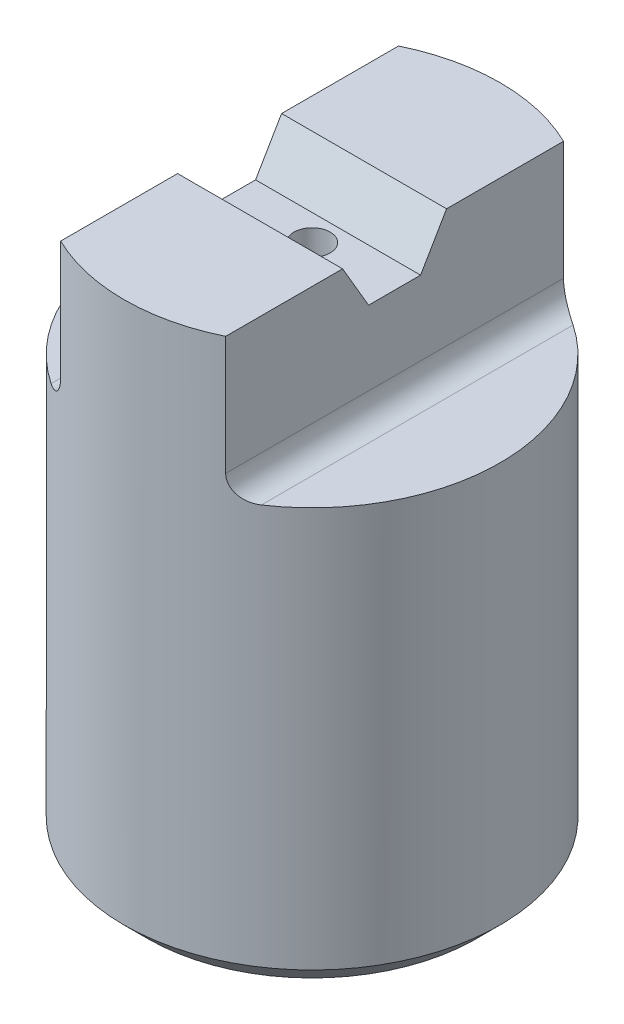
SolidWorks part; units mm, degrees
material "S7"
ref_plane "Alzado" through (0, 0, 0) normal (0, 0, 1) x (1, 0, 0)
ref_plane "Planta" through (0, 0, 0) normal (0, 1, 0) x (1, 0, 0)
ref_plane "Vista lateral" through (0, 0, 0) normal (1, 0, 0) x (0, 0, -1)
sketch "Croquis1" plane through (0, 0, 0) normal (0, 1, 0) x (1, 0, 0)
  circle A0 centre (0, 0) radius 12.6746
  dimension "D1" = 25.3492
extrude "Saliente-Extruir1" add sketch "Croquis1" along normal blind 38.1
sketch "Croquis2" plane through (0, 0, 0) normal (1, 0, 0) x (0, 0, -1)
  line L0 (-3.5052, 38.1) -> (3.5052, 38.1)
  line L1 (12.6746, 38.1) -> (-12.6746, 38.1) construction
  line L2 (3.5052, 38.1) -> (1.7526, 35.1028)
  line L3 (1.7526, 35.1028) -> (-1.7526, 35.1028)
  line L4 (-1.7526, 35.1028) -> (-3.5052, 38.1)
  line L5 (0, 0) -> (0, 35.1028) construction
  line L6 (0, 35.1028) -> (0, 38.1) construction
  dimension "D1" = 2.9972
  dimension "D2" = 3.5052
  dimension "D3" = 7.0104
extrude "Cortar-Extruir1" cut sketch "Croquis2" against normal through all both and the other way through all
sketch "Croquis3" plane through (0, 0, 0) normal (0, 0, 1) x (1, 0, 0)
  line L0 (-12.6746, 28.575) -> (-7.0866, 28.575)
  line L1 (-12.6746, 35.1028) -> (-12.6746, 0) construction
  line L2 (-5.5626, 30.099) -> (-5.5626, 38.1)
  line L3 (12.1803, 38.1) -> (-12.1803, 38.1) construction
  line L4 (-5.5626, 38.1) -> (-12.6746, 38.1)
  line L5 (-12.6746, 38.1) -> (-12.6746, 28.575)
  line L6 (0, 0) -> (0, 38.1) construction
  line L7 (-12.6746, 0) -> (12.6746, 0) construction
  line L8 (12.6746, 38.1) -> (12.6746, 28.575)
  line L9 (5.5626, 38.1) -> (12.6746, 38.1)
  line L10 (5.5626, 30.099) -> (5.5626, 38.1)
  line L11 (12.6746, 28.575) -> (7.0866, 28.575)
  arc A0 (-7.0866, 28.575) -> (-5.5626, 30.099) centre (-7.0866, 30.099) ccw
  arc A1 (7.0866, 28.575) -> (5.5626, 30.099) centre (7.0866, 30.099) cw
  dimension "D1" = 1.524
  dimension "D2" = 9.525
  dimension "D3" = 11.1252
extrude "Cortar-Extruir2" cut sketch "Croquis3" against normal through all both and the other way through all
chamfer "Chaflán1" distance 1.5875 angle 45 1 edges at (0, 0, 12.6746)
sketch "Croquis4" plane through (0, 0, 0) normal (0, -1, 0) x (1, 0, 0)
  circle A0 centre (0, 0) radius 1.2192
  dimension "D1" = 2.4384
extrude "Cortar-Extruir3" cut sketch "Croquis4" against normal through all
hole_wizard "Taladro roscado #8-321" positions "Croquis5" profile "Croquis6" tap size "#8-32" standard "Ansi Inch"
sketch "Croquis5" plane through (0, 0, 0) normal (0, -1, 0) x (-1, 0, 0)
  point P0 (0, 0)
sketch "Croquis6" plane through (0, 0, 0) normal (1, 0, 0) x (0, 0, -1)
  line L0 (0, 0) -> (0, 21.6118)
  line L1 (0, 21.6118) -> (1.7272, 20.574)
  line L2 (1.7272, 20.574) -> (1.7272, 0)
  line L5 (1.7272, 0) -> (0, 0)
  line L10 (0, 21.6118) -> (-1.7272, 20.574) construction
  line L11 (0, -6.35) -> (0, 107.95) construction
  dimension "Diámetro de perforador para roscar" = 3.4544
  dimension "Profundidad de perforador para roscar" = 20.574
  dimension "Ángulo de perforador" = 118
cosmetic thread "Rosca de taladro1" parameters "D1"=9.525, "D2"=4.1656
